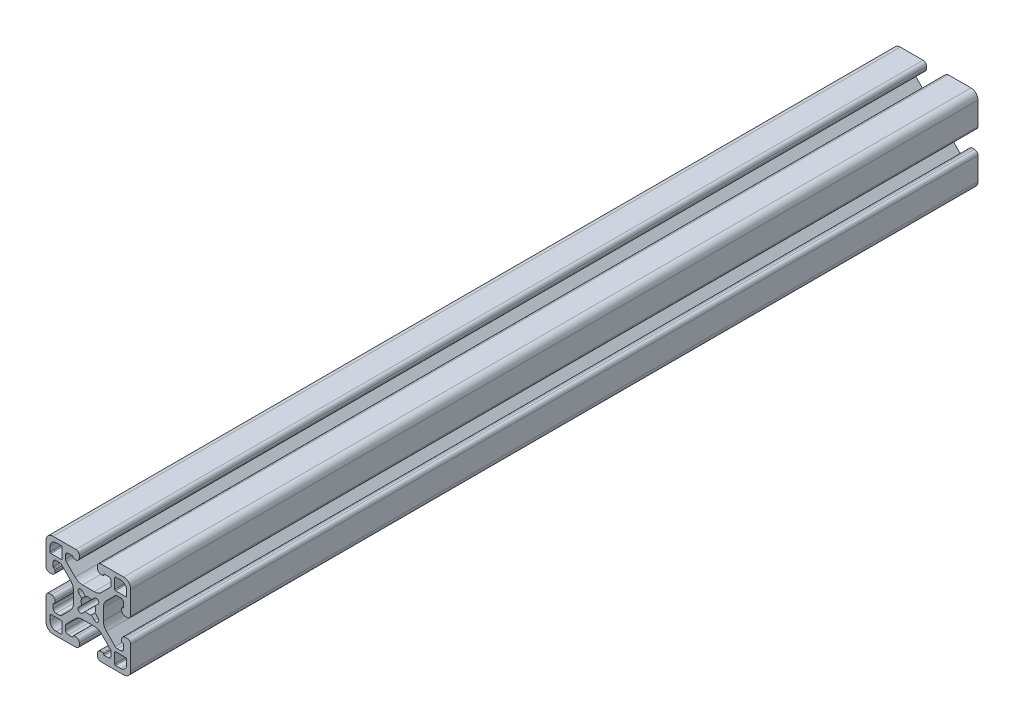
SolidWorks part; units mm, degrees
material "6105-T5 Aluminum"
ref_plane "Front Plane" through (0, 0, 0) normal (0, 0, 1) x (1, 0, 0)
ref_plane "Top Plane" through (0, 0, 0) normal (0, 1, 0) x (1, 0, 0)
ref_plane "Right Plane" through (0, 0, 0) normal (1, 0, 0) x (0, 0, -1)
sketch "Sketch1" plane through (0, 0, 0) normal (0, 0, 1) x (1, 0, 0)
  line L0 (-66.7042, -2.4885) -> (-65.3338, -1.1181)
  line L1 (-65.3338, 1.5948) -> (-66.7042, 2.9652)
  line L2 (-65.0878, 4.5817) -> (-63.7174, 3.2113)
  line L3 (-61.0045, 3.2113) -> (-59.7212, 4.484)
  line L4 (-58.1153, 2.8781) -> (-59.3881, 1.5948)
  line L5 (-59.3881, -1.1181) -> (-58.0176, -2.4885)
  line L6 (-59.6341, -4.1049) -> (-61.0045, -2.7345)
  line L7 (-63.7174, -2.7345) -> (-65.0878, -4.1049)
  line L8 (-79.6075, 12.4812) -> (-79.6075, 14.691)
  line L9 (-76.8135, 17.485) -> (-74.6037, 17.485)
  line L10 (-74.2227, 17.104) -> (-74.2227, 12.4812)
  line L11 (-74.6037, 12.1002) -> (-79.2265, 12.1002)
  line L12 (-74.6037, -17.0082) -> (-76.8135, -17.0082)
  line L13 (-79.6075, -14.2142) -> (-79.6075, -12.0044)
  line L14 (-79.2265, -11.6234) -> (-74.6037, -11.6234)
  line L15 (-74.2227, -12.0044) -> (-74.2227, -16.6272)
  line L16 (-45.1143, -12.0044) -> (-45.1143, -14.2142)
  line L17 (-47.9083, -17.0082) -> (-50.1181, -17.0082)
  line L18 (-50.4991, -16.6272) -> (-50.4991, -12.0044)
  line L19 (-50.1181, -11.6234) -> (-45.4953, -11.6234)
  line L20 (-50.1181, 17.485) -> (-47.9083, 17.485)
  line L21 (-45.1143, 14.691) -> (-45.1143, 12.4812)
  line L22 (-45.4953, 12.1002) -> (-50.1181, 12.1002)
  line L23 (-50.4991, 12.4812) -> (-50.4991, 17.104)
  line L24 (-46.5368, -7.0006) -> (-46.5368, -8.7746)
  line L25 (-47.8067, -10.0486) -> (-49.3926, -10.0486)
  line L26 (-50.2907, -9.6767) -> (-54.2388, -5.7286)
  line L27 (-55.6299, -2.3699) -> (-55.6299, 2.8467)
  line L28 (-54.2388, 6.2053) -> (-50.2907, 10.1534)
  line L29 (-49.3926, 10.5254) -> (-47.8067, 10.5254)
  line L30 (-46.5368, 9.2513) -> (-46.5368, 7.4774)
  line L31 (-46.9178, 7.0964) -> (-46.994, 7.0964)
  line L32 (-47.375, 6.7154) -> (-47.3749, 5.8772)
  line L33 (-45.8001, 4.3024) -> (-44.8857, 4.3024)
  line L34 (-43.3109, 5.8772) -> (-43.3109, 16.1134)
  line L35 (-46.4859, 19.2884) -> (-56.7221, 19.2884)
  line L36 (-58.2969, 17.7136) -> (-58.2969, 16.7992)
  line L37 (-56.7222, 15.2244) -> (-55.884, 15.2244)
  line L38 (-55.503, 15.6054) -> (-55.503, 15.6816)
  line L39 (-55.122, 16.0626) -> (-53.348, 16.0626)
  line L40 (-52.0739, 14.7926) -> (-52.0739, 13.2067)
  line L41 (-52.4459, 12.3087) -> (-56.394, 8.3606)
  line L42 (-59.7526, 6.9694) -> (-64.9693, 6.9694)
  line L43 (-68.3279, 8.3606) -> (-72.276, 12.3087)
  line L44 (-72.6479, 13.2067) -> (-72.6479, 14.7926)
  line L45 (-71.3739, 16.0626) -> (-69.5999, 16.0626)
  line L46 (-69.2189, 15.6816) -> (-69.2189, 15.6054)
  line L47 (-68.8379, 15.2244) -> (-67.9997, 15.2244)
  line L48 (-66.4249, 16.7992) -> (-66.4249, 17.7136)
  line L49 (-67.9997, 19.2884) -> (-78.2359, 19.2884)
  line L50 (-81.4109, 16.1134) -> (-81.4109, 5.8772)
  line L51 (-79.8361, 4.3024) -> (-78.9217, 4.3024)
  line L52 (-77.3469, 5.8772) -> (-77.3469, 6.7154)
  line L53 (-77.7279, 7.0964) -> (-77.8041, 7.0964)
  line L54 (-78.1851, 7.4774) -> (-78.1851, 9.2513)
  line L55 (-76.9151, 10.5254) -> (-75.3293, 10.5254)
  line L56 (-74.4312, 10.1534) -> (-70.4831, 6.2053)
  line L57 (-69.0919, 2.8467) -> (-69.0919, -2.3699)
  line L58 (-70.4831, -5.7286) -> (-74.4312, -9.6767)
  line L59 (-75.3293, -10.0486) -> (-76.9151, -10.0486)
  line L60 (-78.1851, -8.7746) -> (-78.1851, -7.0006)
  line L61 (-77.8041, -6.6196) -> (-77.7279, -6.6196)
  line L62 (-77.3469, -6.2386) -> (-77.3469, -5.4004)
  line L63 (-78.9217, -3.8256) -> (-79.8361, -3.8256)
  line L64 (-81.4109, -5.4004) -> (-81.4109, -15.6366)
  line L65 (-78.2359, -18.8116) -> (-67.9997, -18.8116)
  line L66 (-66.4249, -17.2368) -> (-66.4249, -16.3224)
  line L67 (-67.9997, -14.7476) -> (-68.8379, -14.7476)
  line L68 (-69.2189, -15.1286) -> (-69.2189, -15.2048)
  line L69 (-69.5999, -15.5858) -> (-71.3739, -15.5858)
  line L70 (-72.6479, -14.3158) -> (-72.6479, -12.7299)
  line L71 (-72.276, -11.8319) -> (-68.3279, -7.8838)
  line L72 (-64.9693, -6.4926) -> (-59.7526, -6.4926)
  line L73 (-56.394, -7.8838) -> (-52.4459, -11.8319)
  line L74 (-52.0739, -12.7299) -> (-52.0739, -14.3158)
  line L75 (-53.348, -15.5858) -> (-55.122, -15.5858)
  line L76 (-55.503, -15.2048) -> (-55.503, -15.1286)
  line L77 (-55.884, -14.7476) -> (-56.7222, -14.7476)
  line L78 (-58.2969, -16.3224) -> (-58.2969, -17.2368)
  line L79 (-56.7221, -18.8116) -> (-46.4859, -18.8116)
  line L80 (-43.3109, -15.6366) -> (-43.3109, -5.4004)
  line L81 (-44.8857, -3.8256) -> (-45.8001, -3.8256)
  line L82 (-47.3749, -5.4004) -> (-47.375, -6.2386)
  line L83 (-46.994, -6.6196) -> (-46.9178, -6.6196)
  arc A0 (-66.7042, -2.4885) -> (-65.0878, -4.1049) centre (-65.896, -3.2967) ccw
  arc A1 (-65.3338, 1.5948) -> (-65.3338, -1.1181) centre (-62.3609, 0.2384) ccw
  arc A2 (-65.0878, 4.5817) -> (-66.7042, 2.9652) centre (-65.896, 3.7734) ccw
  arc A3 (-61.0045, 3.2113) -> (-63.7174, 3.2113) centre (-62.3609, 0.2384) ccw
  arc A4 (-58.1153, 2.8781) -> (-59.7212, 4.484) centre (-58.8259, 3.7734) ccw
  arc A5 (-59.3881, -1.1181) -> (-59.3881, 1.5948) centre (-62.3609, 0.2384) ccw
  arc A6 (-59.6341, -4.1049) -> (-58.0176, -2.4885) centre (-58.8259, -3.2967) ccw
  arc A7 (-63.7174, -2.7345) -> (-61.0045, -2.7345) centre (-62.3609, 0.2384) ccw
  arc A8 (-79.6075, 12.4812) -> (-79.2265, 12.1002) centre (-79.2265, 12.4812) ccw
  arc A9 (-76.8135, 17.485) -> (-79.6075, 14.691) centre (-76.8135, 14.691) ccw
  arc A10 (-74.2227, 17.104) -> (-74.6037, 17.485) centre (-74.6037, 17.104) ccw
  arc A11 (-74.6037, 12.1002) -> (-74.2227, 12.4812) centre (-74.6037, 12.4812) ccw
  arc A12 (-74.6037, -17.0082) -> (-74.2227, -16.6272) centre (-74.6037, -16.6272) ccw
  arc A13 (-79.6075, -14.2142) -> (-76.8135, -17.0082) centre (-76.8135, -14.2142) ccw
  arc A14 (-79.2265, -11.6234) -> (-79.6075, -12.0044) centre (-79.2265, -12.0044) ccw
  arc A15 (-74.2227, -12.0044) -> (-74.6037, -11.6234) centre (-74.6037, -12.0044) ccw
  arc A16 (-45.1143, -12.0044) -> (-45.4953, -11.6234) centre (-45.4953, -12.0044) ccw
  arc A17 (-47.9083, -17.0082) -> (-45.1143, -14.2142) centre (-47.9083, -14.2142) ccw
  arc A18 (-50.4991, -16.6272) -> (-50.1181, -17.0082) centre (-50.1181, -16.6272) ccw
  arc A19 (-50.1181, -11.6234) -> (-50.4991, -12.0044) centre (-50.1181, -12.0044) ccw
  arc A20 (-50.1181, 17.485) -> (-50.4991, 17.104) centre (-50.1181, 17.104) ccw
  arc A21 (-45.1143, 14.691) -> (-47.9083, 17.485) centre (-47.9083, 14.691) ccw
  arc A22 (-45.4953, 12.1002) -> (-45.1143, 12.4812) centre (-45.4953, 12.4812) ccw
  arc A23 (-50.4991, 12.4812) -> (-50.1181, 12.1002) centre (-50.1181, 12.4812) ccw
  arc A24 (-47.8067, -10.0486) -> (-46.5368, -8.7746) centre (-47.8067, -8.7786) ccw
  arc A25 (-50.2907, -9.6767) -> (-49.3926, -10.0486) centre (-49.3926, -8.7786) ccw
  arc A26 (-55.6299, -2.3699) -> (-54.2388, -5.7286) centre (-50.8801, -2.3699) ccw
  arc A27 (-54.2388, 6.2053) -> (-55.6299, 2.8467) centre (-50.8801, 2.8467) ccw
  arc A28 (-49.3926, 10.5254) -> (-50.2907, 10.1534) centre (-49.3926, 9.2554) ccw
  arc A29 (-46.5368, 9.2513) -> (-47.8067, 10.5254) centre (-47.8067, 9.2554) ccw
  arc A30 (-46.9178, 7.0964) -> (-46.5368, 7.4774) centre (-46.9178, 7.4774) ccw
  arc A31 (-46.994, 7.0964) -> (-47.375, 6.7154) centre (-46.994, 6.7154) ccw
  arc A32 (-47.3749, 5.8772) -> (-45.8001, 4.3024) centre (-45.8001, 5.8772) ccw
  arc A33 (-44.8857, 4.3024) -> (-43.3109, 5.8772) centre (-44.8857, 5.8772) ccw
  arc A34 (-43.3109, 16.1134) -> (-46.4859, 19.2884) centre (-46.4859, 16.1134) ccw
  arc A35 (-56.7221, 19.2884) -> (-58.2969, 17.7136) centre (-56.7221, 17.7136) ccw
  arc A36 (-58.2969, 16.7992) -> (-56.7222, 15.2244) centre (-56.7221, 16.7992) ccw
  arc A37 (-55.884, 15.2244) -> (-55.503, 15.6054) centre (-55.884, 15.6054) ccw
  arc A38 (-55.122, 16.0626) -> (-55.503, 15.6816) centre (-55.122, 15.6816) ccw
  arc A39 (-52.0739, 14.7926) -> (-53.348, 16.0626) centre (-53.3439, 14.7926) ccw
  arc A40 (-52.4459, 12.3087) -> (-52.0739, 13.2067) centre (-53.3439, 13.2067) ccw
  arc A41 (-59.7526, 6.9694) -> (-56.394, 8.3606) centre (-59.7526, 11.7192) ccw
  arc A42 (-68.3279, 8.3606) -> (-64.9693, 6.9694) centre (-64.9693, 11.7192) ccw
  arc A43 (-72.6479, 13.2067) -> (-72.276, 12.3087) centre (-71.3779, 13.2067) ccw
  arc A44 (-71.3739, 16.0626) -> (-72.6479, 14.7926) centre (-71.3779, 14.7926) ccw
  arc A45 (-69.2189, 15.6816) -> (-69.5999, 16.0626) centre (-69.5999, 15.6816) ccw
  arc A46 (-69.2189, 15.6054) -> (-68.8379, 15.2244) centre (-68.8379, 15.6054) ccw
  arc A47 (-67.9997, 15.2244) -> (-66.4249, 16.7992) centre (-67.9997, 16.7992) ccw
  arc A48 (-66.4249, 17.7136) -> (-67.9997, 19.2884) centre (-67.9997, 17.7136) ccw
  arc A49 (-78.2359, 19.2884) -> (-81.4109, 16.1134) centre (-78.2359, 16.1134) ccw
  arc A50 (-81.4109, 5.8772) -> (-79.8361, 4.3024) centre (-79.8361, 5.8772) ccw
  arc A51 (-78.9217, 4.3024) -> (-77.3469, 5.8772) centre (-78.9217, 5.8772) ccw
  arc A52 (-77.3469, 6.7154) -> (-77.7279, 7.0964) centre (-77.7279, 6.7154) ccw
  arc A53 (-78.1851, 7.4774) -> (-77.8041, 7.0964) centre (-77.8041, 7.4774) ccw
  arc A54 (-76.9151, 10.5254) -> (-78.1851, 9.2513) centre (-76.9151, 9.2554) ccw
  arc A55 (-74.4312, 10.1534) -> (-75.3293, 10.5254) centre (-75.3293, 9.2554) ccw
  arc A56 (-69.0919, 2.8467) -> (-70.4831, 6.2053) centre (-73.8417, 2.8467) ccw
  arc A57 (-70.4831, -5.7286) -> (-69.0919, -2.3699) centre (-73.8417, -2.3699) ccw
  arc A58 (-75.3293, -10.0486) -> (-74.4312, -9.6767) centre (-75.3293, -8.7786) ccw
  arc A59 (-78.1851, -8.7746) -> (-76.9151, -10.0486) centre (-76.9151, -8.7786) ccw
  arc A60 (-77.8041, -6.6196) -> (-78.1851, -7.0006) centre (-77.8041, -7.0006) ccw
  arc A61 (-77.7279, -6.6196) -> (-77.3469, -6.2386) centre (-77.7279, -6.2386) ccw
  arc A62 (-77.3469, -5.4004) -> (-78.9217, -3.8256) centre (-78.9217, -5.4004) ccw
  arc A63 (-79.8361, -3.8256) -> (-81.4109, -5.4004) centre (-79.8361, -5.4004) ccw
  arc A64 (-81.4109, -15.6366) -> (-78.2359, -18.8116) centre (-78.2359, -15.6366) ccw
  arc A65 (-67.9997, -18.8116) -> (-66.4249, -17.2368) centre (-67.9997, -17.2368) ccw
  arc A66 (-66.4249, -16.3224) -> (-67.9997, -14.7476) centre (-67.9997, -16.3224) ccw
  arc A67 (-68.8379, -14.7476) -> (-69.2189, -15.1286) centre (-68.8379, -15.1286) ccw
  arc A68 (-69.5999, -15.5858) -> (-69.2189, -15.2048) centre (-69.5999, -15.2048) ccw
  arc A69 (-72.6479, -14.3158) -> (-71.3739, -15.5858) centre (-71.3779, -14.3158) ccw
  arc A70 (-72.276, -11.8319) -> (-72.6479, -12.7299) centre (-71.3779, -12.7299) ccw
  arc A71 (-64.9693, -6.4926) -> (-68.3279, -7.8838) centre (-64.9693, -11.2424) ccw
  arc A72 (-56.394, -7.8838) -> (-59.7526, -6.4926) centre (-59.7526, -11.2424) ccw
  arc A73 (-52.0739, -12.7299) -> (-52.4459, -11.8319) centre (-53.3439, -12.7299) ccw
  arc A74 (-53.348, -15.5858) -> (-52.0739, -14.3158) centre (-53.3439, -14.3158) ccw
  arc A75 (-55.503, -15.2048) -> (-55.122, -15.5858) centre (-55.122, -15.2048) ccw
  arc A76 (-55.503, -15.1286) -> (-55.884, -14.7476) centre (-55.884, -15.1286) ccw
  arc A77 (-56.7222, -14.7476) -> (-58.2969, -16.3224) centre (-56.7221, -16.3224) ccw
  arc A78 (-58.2969, -17.2368) -> (-56.7221, -18.8116) centre (-56.7221, -17.2368) ccw
  arc A79 (-46.4859, -18.8116) -> (-43.3109, -15.6366) centre (-46.4859, -15.6366) ccw
  arc A80 (-43.3109, -5.4004) -> (-44.8857, -3.8256) centre (-44.8857, -5.4004) ccw
  arc A81 (-45.8001, -3.8256) -> (-47.3749, -5.4004) centre (-45.8001, -5.4004) ccw
  arc A82 (-47.375, -6.2386) -> (-46.994, -6.6196) centre (-46.994, -6.2386) ccw
  arc A83 (-46.5368, -7.0006) -> (-46.9178, -6.6196) centre (-46.9178, -7.0006) ccw
extrude "Extrude1" add sketch "Sketch1" against normal blind 381
